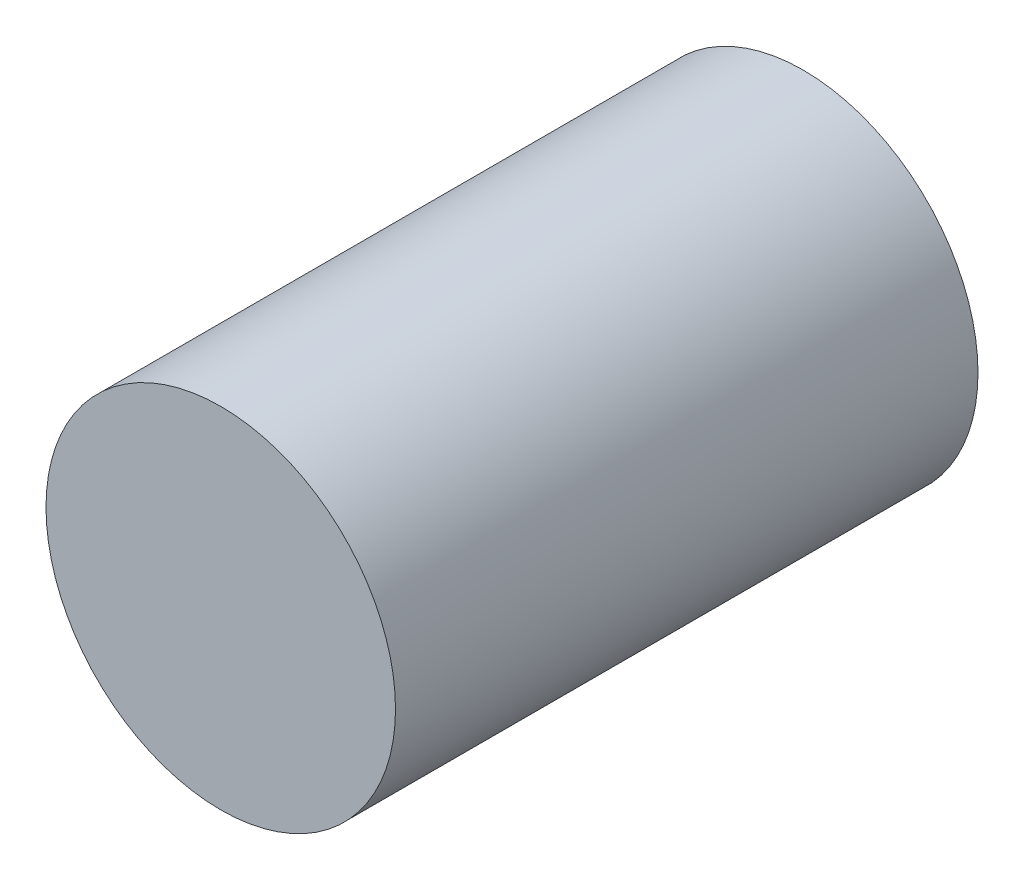
SolidWorks part; units mm, degrees
ref_plane "Front Plane" through (0, 0, 0) normal (0, 0, 1) x (1, 0, 0)
ref_plane "Top Plane" through (0, 0, 0) normal (0, 1, 0) x (1, 0, 0)
ref_plane "Right Plane" through (0, 0, 0) normal (1, 0, 0) x (0, 0, -1)
sketch "Sketch1" plane through (0, 0, 0) normal (0, 0, 1) x (1, 0, 0)
  circle A0 centre (0, 0) radius 0.75
  dimension "D1" = 1.5
extrude "Boss-Extrude1" add sketch "Sketch1" along normal blind 3
sketch "Sketch2" plane through (0, 0, 0) normal (0, 0, -1) x (-1, 0, 0)
  circle A0 centre (0, 0) radius 0.75
extrude "Boss-Extrude2" add sketch "Sketch2" along normal blind 1
sketch "Sketch3" plane through (0, 0, -1) normal (0, 0, -1) x (-1, 0, 0)
  circle A0 centre (0, 0) radius 0.75
extrude "Boss-Extrude3" add sketch "Sketch3" along normal blind 1
sketch "Sketch4" plane through (0, 0, -2) normal (0, 0, -1) x (-1, 0, 0)
  circle A0 centre (0, 0) radius 0.75
extrude "Cut-Extrude1" cut sketch "Sketch4" against normal blind 2.5
